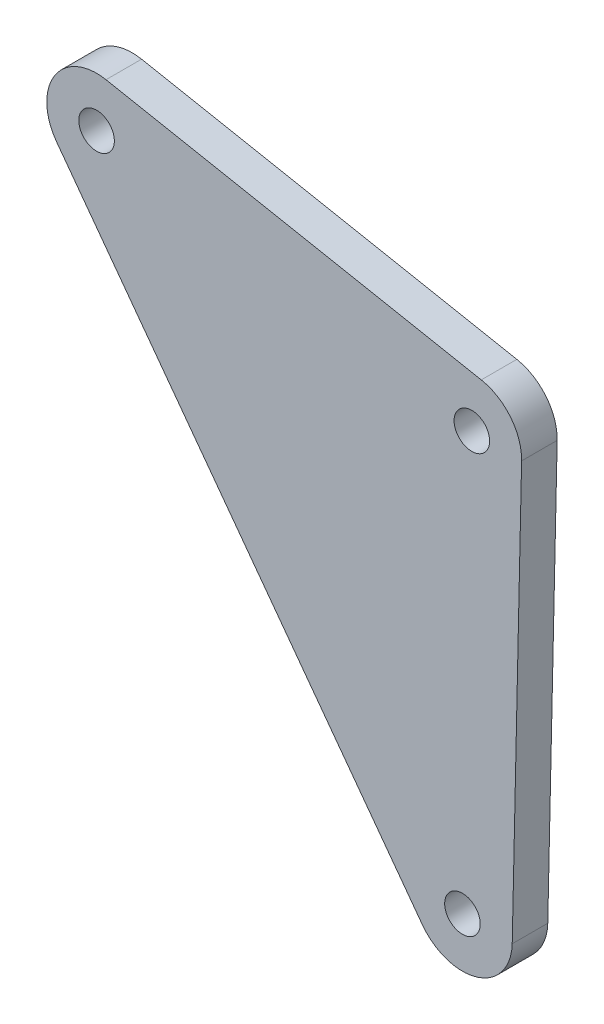
SolidWorks part; units mm, degrees
ref_plane "Front Plane" through (0, 0, 0) normal (0, 0, 1) x (1, 0, 0)
ref_plane "Top Plane" through (0, 0, 0) normal (0, 1, 0) x (1, 0, 0)
ref_plane "Right Plane" through (0, 0, 0) normal (1, 0, 0) x (0, 0, -1)
sketch "Sketch1" plane through (0, 0, 0) normal (0, 0, 1) x (1, 0, 0)
  line L0 (-27.303, -4.5556) -> (39.7131, -17.4736) construction
  line L1 (39.7131, -17.4736) -> (38.0347, -92.9945) construction
  line L2 (38.0347, -92.9945) -> (-27.303, -4.5556) construction
  line L3 (-47.9909, 8.4858) -> (48.7677, -10.1653)
  line L4 (48.7677, -10.1653) -> (46.3444, -119.2032)
  line L5 (46.3444, -119.2032) -> (-47.9909, 8.4858)
  circle A0 centre (-27.303, -4.5556) radius 3.175
  circle A1 centre (39.7131, -17.4736) radius 3.175
  circle A2 centre (38.0347, -92.9945) radius 3.175
  dimension "D4" = 6.35
  dimension "D1" = 68.2498
  dimension "D2" = 75.5396
  dimension "D3" = 109.9566
  dimension "D5" = 8.89
extrude "Boss-Extrude1" add sketch "Sketch1" along normal blind 6.35
fillet "Fillet1" radius 8.89 3 edges at (46.3444, -119.2032, 3.175) (-47.9909, 8.4858, 3.175) (48.7677, -10.1653, 3.175)
